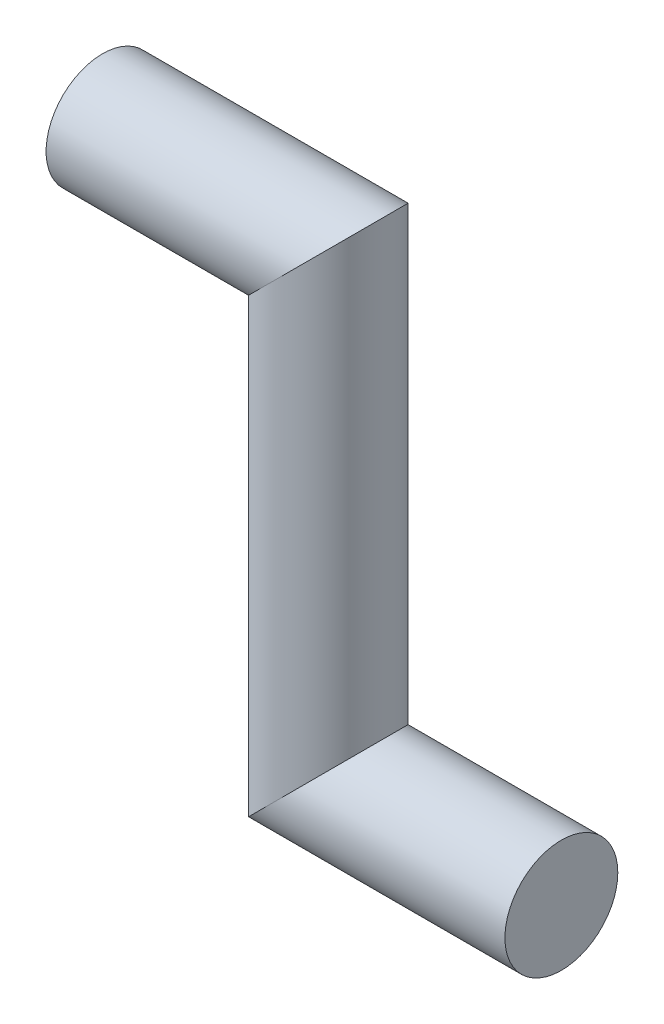
SolidWorks part; units mm, degrees
ref_plane "前视基准面" through (0, 0, 0) normal (0, 0, 1) x (1, 0, 0)
ref_plane "上视基准面" through (0, 0, 0) normal (0, 1, 0) x (1, 0, 0)
ref_plane "右视基准面" through (0, 0, 0) normal (1, 0, 0) x (0, 0, -1)
sketch "草图1" plane through (0, 0, 0) normal (1, 0, 0) x (0, 0, -1)
  circle A0 centre (0, 0) radius 2.5
sketch "草图2" plane through (0, 0, 0) normal (0, 0, 1) x (1, 0, 0)
  line L0 (0, 0) -> (10, 0)
  line L1 (10, 0) -> (10, -20)
  line L2 (10, -20) -> (20.32, -20)
  dimension "D1" = 10
  dimension "D2" = 20
  dimension "D3" = 10.32
sweep "扫描1" add profiles "草图1" path "草图2"
